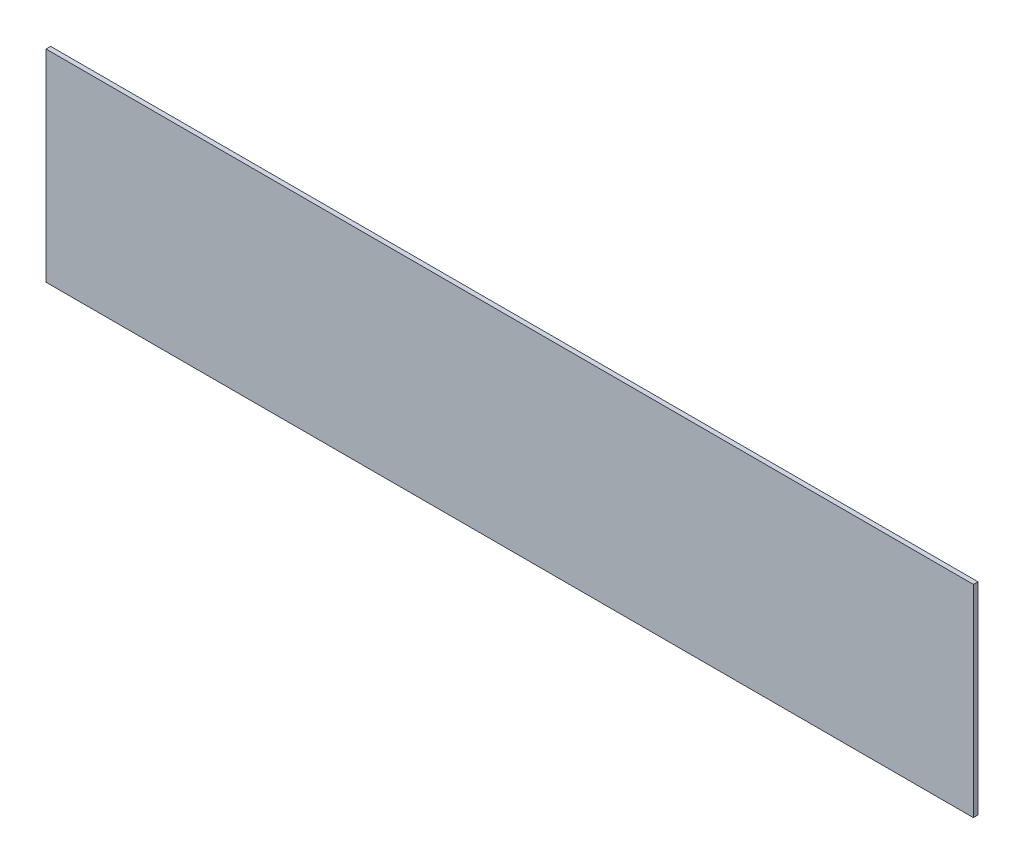
SolidWorks part; units mm, degrees
ref_plane "Front Plane" through (0, 0, 0) normal (0, 0, 1) x (1, 0, 0)
ref_plane "Top Plane" through (0, 0, 0) normal (0, 1, 0) x (1, 0, 0)
ref_plane "Right Plane" through (0, 0, 0) normal (1, 0, 0) x (0, 0, -1)
sketch "Sketch1" plane through (0, 0, 0) normal (0, 0, 1) x (1, 0, 0)
  line L1 (-1010, -220) -> (1010, -220)
  line L2 (-1010, -220) -> (-1010, 220)
  line L3 (-1010, 220) -> (1010, 220)
  line L4 (1010, -220) -> (1010, 220)
  line L5 (-1010, -220) -> (1010, 220) construction
  line L6 (-1010, 220) -> (1010, -220) construction
  point P0 (0, 0)
  dimension "D1" = 2020
  dimension "D2" = 440
extrude "Boss-Extrude1" add sketch "Sketch1" along normal blind 10
